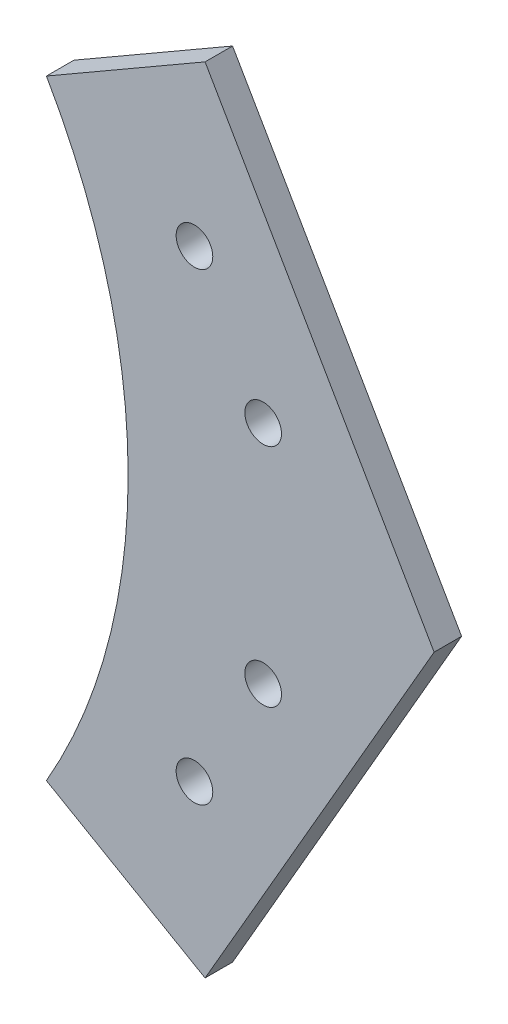
SolidWorks part; units mm, degrees
ref_plane "前视基准面" through (0, 0, 0) normal (0, 0, 1) x (1, 0, 0)
ref_plane "上视基准面" through (0, 0, 0) normal (0, 1, 0) x (1, 0, 0)
ref_plane "右视基准面" through (0, 0, 0) normal (1, 0, 0) x (0, 0, -1)
sketch "草图1" plane through (0, 0, 0) normal (0, 0, 1) x (1, 0, 0)
  line L0 (30.8746, -1.113) -> (5.8746, 42.1883)
  line L1 (5.8746, 42.1883) -> (-11.4459, 32.1883)
  line L2 (-11.4459, -34.4142) -> (5.8746, -44.4142)
  line L3 (5.8746, -44.4142) -> (30.8746, -1.113)
  circle A0 centre (4.7144, -26.4239) radius 2
  arc A1 (-11.4459, -34.4142) -> (-11.4459, 32.1883) centre (-69.1254, -1.113) ccw
  circle A2 centre (12.2144, -13.4335) radius 2
  circle A3 centre (12.2144, 11.2075) radius 2
  circle A4 centre (4.7144, 24.1979) radius 2
extrude "凸台-拉伸1" add sketch "草图1" along normal blind 3
